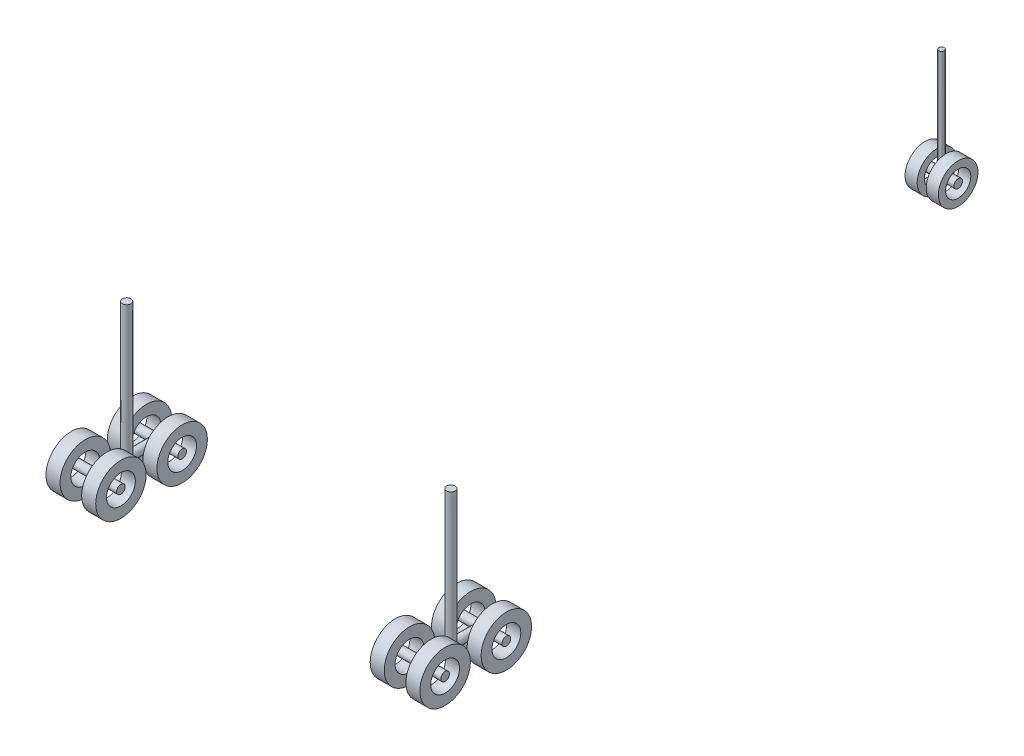
SolidWorks part; units mm, degrees
other "DetailItem1" parameters "RD1"=24.5989, "RD3"=24384, "RD4"=17538.8642, "RD5"=2725.3831, "RD6"=31107.4169, "RD7"=56568.0005, "RD2"=21.978, "RD8"=19.396
ref_plane "Front Plane" through (0, 0, 0) normal (0, 0, 1) x (1, 0, 0)
ref_plane "Top Plane" through (0, 0, 0) normal (0, 1, 0) x (1, 0, 0)
ref_plane "Right Plane" through (0, 0, 0) normal (1, 0, 0) x (0, 0, -1)
sketch "Sketch2" plane through (0, 0, 0) normal (0, 1, 0) x (1, 0, 0)
  line L0 (0, -6122.228) -> (0, 2040.7427)
  line L1 (0, 0) -> (-18096.1342, 0) construction
  line L2 (0, 0) -> (-21640.8, -16307.5125) construction
  line L3 (-21640.8, -18450.2946) -> (-21640.8, -15593.2518)
  line L4 (-21640.8, -15593.2518) -> (0, 2040.7427)
  line L5 (-21640.8, -18450.2946) -> (0, -6122.228)
  line L6 (-9083.802, -5361.1886) -> (-9083.802, -6845.1358) construction
  line L7 (-9083.802, -6845.1358) -> (-9083.802, -11296.9774) construction
  line L8 (-9083.802, -6845.1358) -> (0, -6845.1358) construction
  line L9 (0, 408.1485) -> (-18440.4, -13713.752)
  line L10 (0, -35661.6) -> (-7316.724, -42249.6079) construction
  line L11 (0, -35661.6) -> (-8167.6786, -35661.6) construction
  line L12 (0, -34539.0879) -> (0, -39029.1363)
  line L13 (-7316.724, -43428.2455) -> (-7316.724, -41856.7287)
  line L14 (-7316.724, -41856.7287) -> (0, -34539.0879)
  line L15 (0, -39029.1363) -> (-7316.724, -43428.2455)
  line L16 (-2544.3607, -37083.7674) -> (-2544.3607, -37952.5526) construction
  line L17 (-2544.3607, -37952.5526) -> (-2544.3607, -40558.9084) construction
  line L18 (-2544.3607, -37952.5526) -> (0, -37952.5526) construction
  line L19 (-18440.4, -13713.752) -> (-18440.4, -15898.787)
  line L20 (-18440.4, -15898.787) -> (0, -4489.6339)
  line L21 (0, 408.1485) -> (0, -4489.6339) construction
  line L22 (0, -4489.6339) -> (0, 408.1485) construction
  line L23 (0, 408.1485) -> (0, -2040.7427) construction
  line L24 (0, 408.1485) -> (0, -4489.6339) construction
  line L25 (0, -2040.7427) -> (-18440.4, -14806.2695) construction
  line L26 (0, 408.1485) -> (-21640.8, -16164.6603) construction
  line L27 (-6975.7046, -4933.9377) -> (-6975.7046, -6869.7347) construction
  line L28 (-6975.7046, -6869.7347) -> (-6975.7046, -8805.5317) construction
  line L29 (-6975.7046, -6869.7347) -> (0, -6869.7347) construction
  dimension "Wing Sweep" = 37
  dimension "Half Span" = 21640.8
  dimension "Wing Root" = 8162.9707
  dimension "D4" = 2040.7427
  dimension "Wing Tip" = 2857.0428
  dimension "D6" = 714.2607
  dimension "Wing YBar" = 9083.802
  dimension "Tail Sweep" = 42
  dimension "Tail Root" = 4490.0484
  dimension "D10" = 1122.5121
  dimension "Tail Tip" = 1571.5168
  dimension "D12" = 392.8792
  dimension "D13" = 7316.724
  dimension "Tail Ybar" = 2544.3607
  dimension "First Spar" = 1632.5941
  dimension "Second Spar" = 6530.3766
  dimension "Fuel Tip" = 2185.035
  dimension "Tip Spar" = 571.4086
  dimension "Fuel Ybar" = 6975.7046
  dimension "Fuel Tank Length" = 18440.4
  dimension "Tail Arm" = 35661.6
sketch "Sketch4" plane through (0, 0, 0) normal (0, 1, 0) x (1, 0, 0)
  line L0 (0, 17538.8642) -> (0, -40677.9358) construction
  line L1 (-2194.56, 17538.8642) -> (2194.56, 17538.8642) construction
  line L2 (-2194.56, 10955.1842) -> (-2194.56, -31899.6958)
  line L3 (-2194.56, -40677.9358) -> (2194.56, -40677.9358) construction
  line L4 (2194.56, 10955.1842) -> (2194.56, -31899.6958)
  line L5 (0, -6122.228) -> (0, 2040.7427) construction
  line L6 (-9083.802, -6845.1358) -> (0, -6845.1358) construction
  line L7 (-2544.3607, -37952.5526) -> (0, -37952.5526) construction
  line L8 (0, 0) -> (-21640.8, -16307.5125) construction
  line L9 (-21640.8, -15593.2518) -> (0, 2040.7427) construction
  line L10 (-8474.964, 1555.5245) -> (-5807.964, 1555.5245)
  line L11 (-8474.964, 1555.5245) -> (-8474.964, -5453.2245)
  line L12 (-8474.964, -5453.2245) -> (-5807.964, -5453.2245)
  line L13 (-5807.964, 1555.5245) -> (-5807.964, -5453.2245)
  line L14 (2194.56, 10955.1842) -> (-2194.56, 10955.1842)
  arc A0 (-2194.56, -31899.6958) -> (2194.56, -31899.6958) centre (0, -31899.6958) ccw construction
  spline S0 degree 2 poles (-2194.56, 10955.1842) (-2319.3121, 14550.827) (0, 17538.8642) knots 0 0 0 1 1 1 construction
  spline S1 degree 2 poles (2194.56, 10955.1842) (2319.3121, 14550.827) (0, 17538.8642) knots 0 0 0 1 1 1 construction
  spline S2 degree 3 poles (-2194.56, -31899.6958) (-2185.0252, -17343.0176) (-1882.3736, -55849.4008) (-475.0937, -22625.7195) (0, -39029.1363) knots 0 0 0 0 0.566127 1 1 1 1 construction
  spline S3 degree 3 poles (2194.56, -31899.6958) (2185.0252, -17343.0176) (1882.3736, -55849.4008) (475.0937, -22625.7195) (0, -39029.1363) knots 0 0 0 0 0.566127 1 1 1 1 construction
  spline S4 degree 2 poles (-2194.56, -31899.6958) (-4104.2514, -24790.3016) (0, -27753.3552) knots 0 0 0 1 1 1
  spline S5 degree 2 poles (2194.56, -31899.6958) (4104.2514, -24790.3016) (0, -27753.3552) knots 0 0 0 1 1 1
  point P6 (0, 10955.1842)
  point P7 (0, -31899.6958)
  point P8 (0, -6845.1358)
  point P15 (0, -34094.2558)
  point P28 (-7141.464, 1555.5245)
  point P29 (-7141.464, -3778.4755)
  point P35 (-7141.464, -5381.4791)
  point P44 (-7141.464, -1247.9751)
  dimension "Fuse Length" = 58216.8
  dimension "Fuse Dia" = 4389.12
  dimension "D3" = 6583.68
  dimension "D4" = 8778.24
  dimension "D6" = 7141.464
  dimension "Engine Dia" = 2667
  dimension "Engine Length" = 7008.749
  dimension "D9" = 5334
  dimension "D10" = 2803.4996
  dimension "D11" = 5597.1607
  dimension "D2" = 24384
ref_plane "Plane1" through (0, 609.6, 0) normal (0, 1, 0) x (1, 0, 0)
sketch "Sketch10" plane through (0, 0, 0) normal (0, 1, 0) x (1, 0, 0)
  line L0 (-21640.8, -15593.2518) -> (-2194.56, 252.5066)
  line L1 (-2194.56, 10955.1842) -> (-2194.56, -31899.6958) construction
  line L2 (-21640.8, -15593.2518) -> (-21640.8, -18450.2946)
  line L3 (-21640.8, -18450.2946) -> (-7141.464, -10190.49)
  line L4 (-7141.464, -10190.49) -> (-2194.56, -10190.49)
  line L5 (-21640.8, -18450.2946) -> (0, -6122.228) construction
  line L6 (-21640.8, -15593.2518) -> (0, 2040.7427) construction
  line L7 (-2194.56, -10190.49) -> (-2194.56, 252.5066) construction
  line L9 (0, 271.2873) -> (0, -10190.49)
  line L10 (0, -10190.49) -> (-2194.56, -10190.49)
  line L11 (0, -6122.228) -> (0, 2040.7427) construction
  line L12 (-2194.56, 252.5066) -> (0, 2040.7427)
  line L13 (0, 2040.7427) -> (0, 271.2873)
sketch "Sketch11" plane through (0, 0, 0) normal (0, 1, 0) x (1, 0, 0)
  line L0 (0, 17538.8642) -> (0, -40677.9358) construction
  point P0 (0, -6845.1358)
  dimension "D1" = 24384
ref_plane "Plane3" through (0, 1731.482, 0) normal (0, 1, 0) x (1, 0, 0)
sketch "Sketch12" plane through (0, 0, 0) normal (0, 1, 0) x (1, 0, 0)
  line L0 (0, 17538.8642) -> (0, -40677.9358) construction
  line L1 (-127, 11129.9847) -> (127, 11129.9847) construction
  line L2 (-127, 11129.9847) -> (-127, 10780.3837) construction
  line L3 (-127, 10780.3837) -> (127, 10780.3837) construction
  line L4 (127, 11129.9847) -> (127, 10780.3837) construction
  line L5 (-127, 11129.9847) -> (127, 10780.3837) construction
  line L6 (-127, 10780.3837) -> (127, 11129.9847) construction
  line L7 (-4572, -7454.7358) -> (0, 10955.1842) construction
  line L8 (-4876.8, -7035.2146) -> (-4267.2, -7035.2146) construction
  line L9 (-4876.8, -7035.2146) -> (-4876.8, -7874.257) construction
  line L10 (-4876.8, -7874.257) -> (-4267.2, -7874.257) construction
  line L11 (-4267.2, -7035.2146) -> (-4267.2, -7874.257) construction
  line L12 (-4876.8, -7035.2146) -> (-4267.2, -7874.257) construction
  line L13 (-4876.8, -7874.257) -> (-4267.2, -7035.2146) construction
  line L14 (-4572, -7454.7358) -> (0, -7454.7358) construction
  line L15 (-4572, -7454.7358) -> (0, -8590.1663) construction
  line L16 (-4572, -7035.2146) -> (-4572, -7874.257) construction
  line L17 (-4572, -7454.7358) -> (-762, -7454.7358) construction
  line L19 (-1389.4421, -8318.3358) -> (-134.5579, -8318.3358) construction
  line L20 (-1389.4421, -8318.3358) -> (-1389.4421, -6591.1358) construction
  line L21 (-1389.4421, -6591.1358) -> (-134.5579, -6591.1358) construction
  line L22 (-134.5579, -8318.3358) -> (-134.5579, -6591.1358) construction
  line L23 (-1389.4421, -8318.3358) -> (-134.5579, -6591.1358) construction
  line L24 (-1389.4421, -6591.1358) -> (-134.5579, -8318.3358) construction
  circle A0 centre (-4572, -7454.7358) radius 121.92
  circle A1 centre (-1389.4421, -8318.3358) radius 711.2 construction
  circle A4 centre (-1389.4421, -6591.1358) radius 711.2 construction
  point P0 (0, 10955.1842)
  point P7 (-4572, -7454.7358)
  point P30 (-1389.4421, -7302.3358)
  point P31 (-1389.4421, -7607.1358)
  point P39 (-762, -7454.7358)
  dimension "D8" = 243.84
  dimension "D9" = 304.8
  dimension "D11" = 1422.4
  dimension "D1" = 4572
  dimension "D2" = 90
  dimension "D3" = 36
  dimension "D4" = 36
  dimension "D5" = 254
  dimension "D6" = 609.6
  dimension "D7" = 609.6
  dimension "D10" = 36
  dimension "D12" = 3810
ref_plane "Plane2" through (-4572, 0, 7454.7358) normal (0.241, 0, -0.9705) x (-0.9705, 0, -0.241)
sketch "Sketch13" plane through (0, 1731.482, 0) normal (0, 1, 0) x (1, 0, 0)
  line L1 (0, -6122.228) -> (0, 2040.7427) construction
  point P0 (0, -6845.1358)
  dimension "D1" = 0
sketch "Sketch14" plane through (-4572, 0, 7454.7358) normal (0.241, 0, -0.9705) x (-0.9705, 0, -0.241)
  line L0 (0, 0) -> (-4290.287, 1731.482) construction
  line L1 (0, 0) -> (-5277.159, 0) construction
  dimension "D1" = 21.978
ref_plane "Plane4" through (-4572, 0, 0) normal (-1, 0, 0) x (0, 0, 1)
sketch "Sketch15" plane through (-4572, 0, 0) normal (-1, 0, 0) x (0, 0, 1)
  line L0 (7454.7358, 0) -> (6845.1358, 1731.482) construction
  line L1 (7454.7358, 0) -> (7454.7358, 1731.482) construction
ref_plane "Plane5" through (-4876.8, 0, 0) normal (1, 0, 0) x (0, 0, -1)
sketch "Sketch16" plane through (-4876.8, 0, 0) normal (1, 0, 0) x (0, 0, -1)
  line L0 (-7454.7358, 0) -> (-6591.1358, 0) construction
  line L2 (-7454.7358, 0) -> (-7454.7358, 631.3043) construction
  line L3 (-7454.7358, 0) -> (-8318.3358, 0) construction
  circle A0 centre (-6591.1358, 0) radius 711.2
  circle A1 centre (-8318.3358, 0) radius 711.2
  circle A3 centre (-6591.1358, 0) radius 406.4
  circle A4 centre (-8318.3358, 0) radius 406.4
  point P3 (-7607.1358, 0)
  point P8 (-7454.7358, 0)
  point P9 (-7302.3358, 0)
  dimension "D1" = 1422.4
  dimension "D3" = 812.8
  dimension "D2" = 304.8
extrude "Boss-Extrude1" add sketch "Sketch16" against normal blind 396.24
ref_plane "Plane6" through (-4572, 0, 0) normal (1, 0, 0) x (0, 0, -1)
mirror "Mirror2" about plane through (-4572, 0, 0) normal (1, 0, 0) of bodies 132 133
extrude "Boss-Extrude2" add sketch "Sketch12" along normal blind 3810
sketch "Sketch17" plane through (-5273.04, 0, 0) normal (-1, 0, 0) x (0, 0, 1)
  circle A0 centre (6591.1358, 0) radius 121.92
  circle A1 centre (6591.1358, 0) radius 406.4 construction
  circle A2 centre (8318.3358, 0) radius 121.92
  circle A3 centre (8318.3358, 0) radius 406.4 construction
  dimension "D1" = 243.84
extrude "Boss-Extrude3" add sketch "Sketch17" against normal up to surface (1402.08 mm away) separate body up to face at (-3870.96, 0, 8724.7358)
ref_plane "Plane7" through (0, 0, 7454.7358) normal (0, 0, 1) x (1, 0, 0)
sketch "Sketch18" plane through (0, 0, 7454.7358) normal (0, 0, 1) x (1, 0, 0)
  circle A0 centre (-4572, 0) radius 121.92
  dimension "D1" = 243.84
extrude "Boss-Extrude4" add sketch "Sketch18" along normal blind 762 and the other way blind 762
ref_plane "Plane8" through (-127, 0, 0) normal (1, 0, 0) x (0, 0, -1)
sketch "Sketch19" plane through (-127, 0, 0) normal (1, 0, 0) x (0, 0, -1)
  line L0 (11129.9847, 0) -> (10780.3837, 0) construction
  circle A0 centre (10955.1842, 0) radius 558.8
  circle A1 centre (10955.1842, 0) radius 355.6
  dimension "D1" = 1117.6
  dimension "D2" = 711.2
extrude "Boss-Extrude5" add sketch "Sketch19" against normal blind 342.9 separate body
mirror "Mirror4" about plane through (0, 0, 0) normal (1, 0, 0) of bodies 141 133 132 135 140 134
sketch "Sketch20" plane through (-469.9, 0, 0) normal (-1, 0, 0) x (0, 0, 1)
  circle A0 centre (-10955.1842, 0) radius 121.92
  circle A1 centre (6591.1358, 0) radius 121.92 construction
  circle A2 centre (-10955.1842, 0) radius 355.6 construction
extrude "Boss-Extrude6" add sketch "Sketch20" against normal up to surface (939.8 mm away) separate body up to face at (469.9, 0, -11310.7842)
sketch "Sketch21" plane through (0, 0, 0) normal (0, 1, 0) x (1, 0, 0)
  circle A0 centre (0, 10955.1842) radius 76.2
extrude "Boss-Extrude7" add sketch "Sketch21" along normal blind 3048
sketch "Sketch23" plane through (0, 3810, 0) normal (0, 1, 0) x (1, 0, 0)
  circle A0 centre (0, -6845.1358) radius 469.6531 construction
  point P0 (0, -6845.1358)
  point P3 (0, -6845.1358)
sketch "Sketch24" plane through (-469.9, 0, 0) normal (-1, 0, 0) x (0, 0, 1)
  line L0 (-10955.1842, 0) -> (-10955.1842, 3048) construction
  line L1 (-10878.9842, 3048) -> (-11031.3842, 3048) construction
sketch "Sketch25" plane through (0, 0, 0) normal (0, 1, 0) x (1, 0, 0)
  line L0 (-762, -7581.7358) -> (-762, -7327.7358) construction
  line L1 (-4572, -7454.7358) -> (0, -7454.7358) construction
  line L2 (-762, -7454.7358) -> (-4572, -7454.7358) construction
  line L3 (0, 10955.1842) -> (0, 14003.1842) construction
  line L4 (-127, 14561.9842) -> (-127, 13444.3842) construction
  line L5 (-127, 14561.9842) -> (-469.9, 14561.9842) construction
  line L6 (-127, 13444.3842) -> (-469.9, 13444.3842) construction
  line L7 (-469.9, 14561.9842) -> (-469.9, 13444.3842) construction
  line L8 (-127, 14561.9842) -> (-469.9, 13444.3842) construction
  line L9 (-127, 13444.3842) -> (-469.9, 14561.9842) construction
  line L10 (127, 14561.9842) -> (127, 13444.3842) construction
  line L11 (127, 14561.9842) -> (469.9, 14561.9842) construction
  line L12 (127, 13444.3842) -> (469.9, 13444.3842) construction
  line L13 (469.9, 14561.9842) -> (469.9, 13444.3842) construction
  line L14 (127, 14561.9842) -> (469.9, 13444.3842) construction
  line L15 (127, 13444.3842) -> (469.9, 14561.9842) construction
  line L16 (0, 14003.1842) -> (127, 14003.1842) construction
  line L17 (0, 14003.1842) -> (-127, 14003.1842) construction
  line L18 (0, -2486.66) -> (0, 2486.66) construction
  line L19 (762, -7454.7358) -> (4572, -7454.7358) construction
  line L20 (762, -7581.7358) -> (762, -7327.7358) construction
  circle A0 centre (-762, -6616.5358) radius 711.2 construction
  circle A1 centre (-762, -8292.9358) radius 711.2 construction
  circle A2 centre (762, -8292.9358) radius 711.2 construction
  circle A3 centre (762, -6616.5358) radius 711.2 construction
  point P4 (-762, -7327.7358)
  point P5 (-762, -7581.7358)
  point P8 (-762, -7454.7358)
  point P19 (-298.45, 14003.1842)
  point P20 (298.45, 14003.1842)
  point P21 (-298.45, 13236.793)
  point P41 (762, -7581.7358)
  point P42 (762, -7327.7358)
  dimension "D1" = 1422.4
  dimension "D2" = 254
  dimension "D3" = 3810
  dimension "D4" = 1117.6
  dimension "D5" = 342.9
  dimension "D6" = 254
  dimension "D7" = 3048
sketch "Sketch26" plane through (0, 0, 0) normal (1, 0, 0) x (0, 0, -1)
  line L0 (10955.1842, 3048) -> (13980.6253, 3418.1492) construction
  line L1 (11031.3842, 3048) -> (10878.9842, 3048) construction
  line L2 (11031.3842, 3048) -> (10878.9842, 3048) construction
  circle A0 centre (14539.4253, 3418.1492) radius 558.8 construction
  point P2 (0, 0)
  point P7 (13980.6253, 3418.1492)
  point P8 (13980.6253, 3418.1492)
  dimension "D2" = 1117.6
  dimension "D1" = 3048
equation "\"D6@Sketch2\" = \"Wing Tip@Sketch2\" / 4"
equation "\"D4@Sketch2\" = \"Wing Root@Sketch2\" / 4"
equation "\"D10@Sketch2\" = \"Tail Root@Sketch2\" / 4"
equation "\"D12@Sketch2\" = \"Tail Tip@Sketch2\" / 4"
equation "\"D13@Sketch2\"=48.01/2"
equation "\"First Spar@Sketch2\"=0.2 * \"Wing Root@Sketch2\""
equation "\"Second Spar@Sketch2\"    = 0.8 * \"Wing Root@Sketch2\""
equation "\"Tip Spar@Sketch2\"=0.2 * \"Wing Tip@Sketch2\""
equation "\"D3@Sketch4\" = 1.5 * \"Fuse Dia@Sketch4\""
equation "\"D4@Sketch4\" = 2 * \"Fuse Dia@Sketch4\""
equation "\"D6@Sketch4\" = 0.33 * \"Half Span@Sketch2\""
equation "\"D9@Sketch4\" = 2 * \"Engine Dia@Sketch4\""
equation "\"D10@Sketch4\" = 0.40 * \"Engine Length@Sketch4\""
